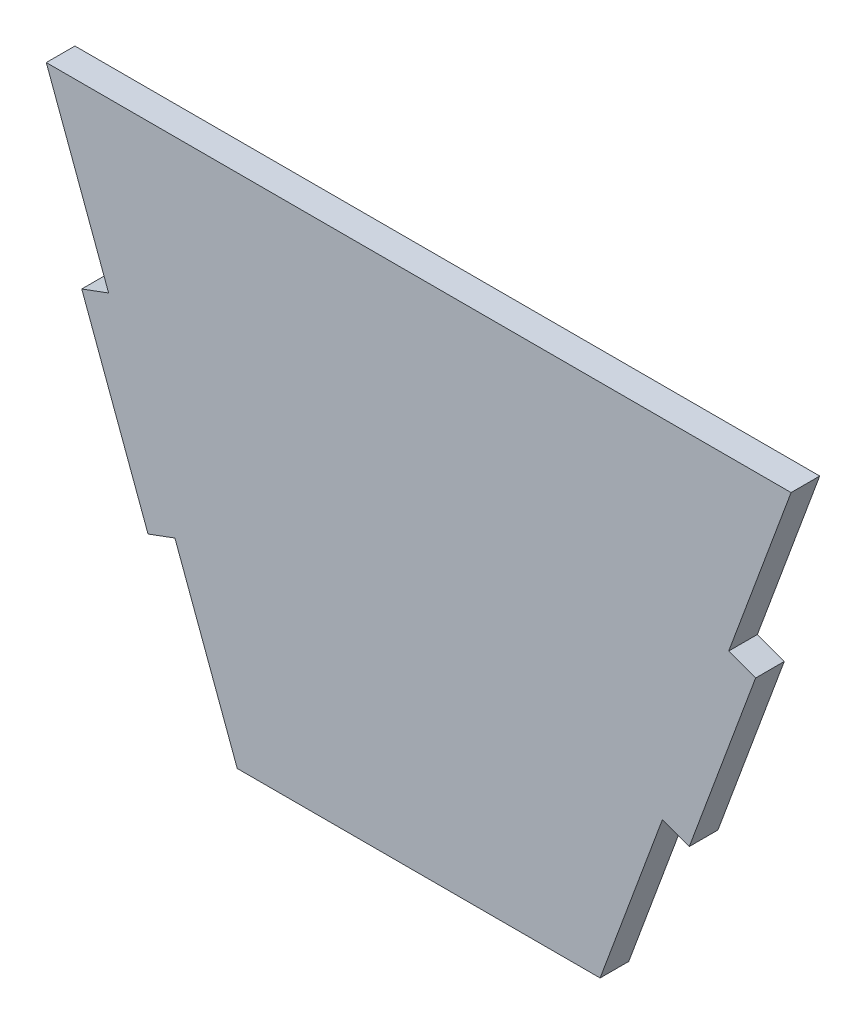
SolidWorks part; units mm, degrees
ref_plane "Plan de face" through (0, 0, 0) normal (0, 0, 1) x (1, 0, 0)
ref_plane "Plan de dessus" through (0, 0, 0) normal (0, 1, 0) x (1, 0, 0)
ref_plane "Plan de droite" through (0, 0, 0) normal (1, 0, 0) x (0, 0, -1)
sketch "Esquisse1" plane through (0, 0, 0) normal (0, 0, 1) x (1, 0, 0)
  line L0 (0, 0) -> (78, 0)
  line L1 (6.5284, -17.6354) -> (0, 0)
  line L2 (20, -54.027) -> (58, -54.027)
  line L3 (64.5284, -36.3915) -> (58, -54.027)
  line L4 (6.5284, -17.6354) -> (3.715, -18.6769)
  line L5 (13.4716, -36.3915) -> (10.6582, -37.433)
  line L6 (10.6582, -37.433) -> (3.715, -18.6769)
  line L7 (13.4716, -36.3915) -> (20, -54.027)
  line L8 (64.5284, -36.3915) -> (67.3418, -37.433)
  line L9 (67.3418, -37.433) -> (74.285, -18.6769)
  line L10 (74.285, -18.6769) -> (71.4716, -17.6354)
  line L11 (71.4716, -17.6354) -> (78, 0)
  dimension "D1" = 78
  dimension "D2" = 38
  dimension "D3" = 90
  dimension "D4" = 57.61
  dimension "D5" = 90
  dimension "D6" = 90
  dimension "D7" = 3
  dimension "D8" = 3
  dimension "D9" = 57.61
  dimension "D10" = 18.805
  dimension "D11" = 18.805
  dimension "D12" = 90
  dimension "D13" = 18.805
  dimension "D14" = 18.805
  dimension "D15" = 69.686
  dimension "D16" = 3
  dimension "D17" = 3
  dimension "D18" = 69.686
  dimension "D19" = 90
  dimension "D20" = 90
  dimension "D21" = 90
  dimension "D22" = 90
extrude "Boss.-Extru.1" add sketch "Esquisse1" along normal blind 3
